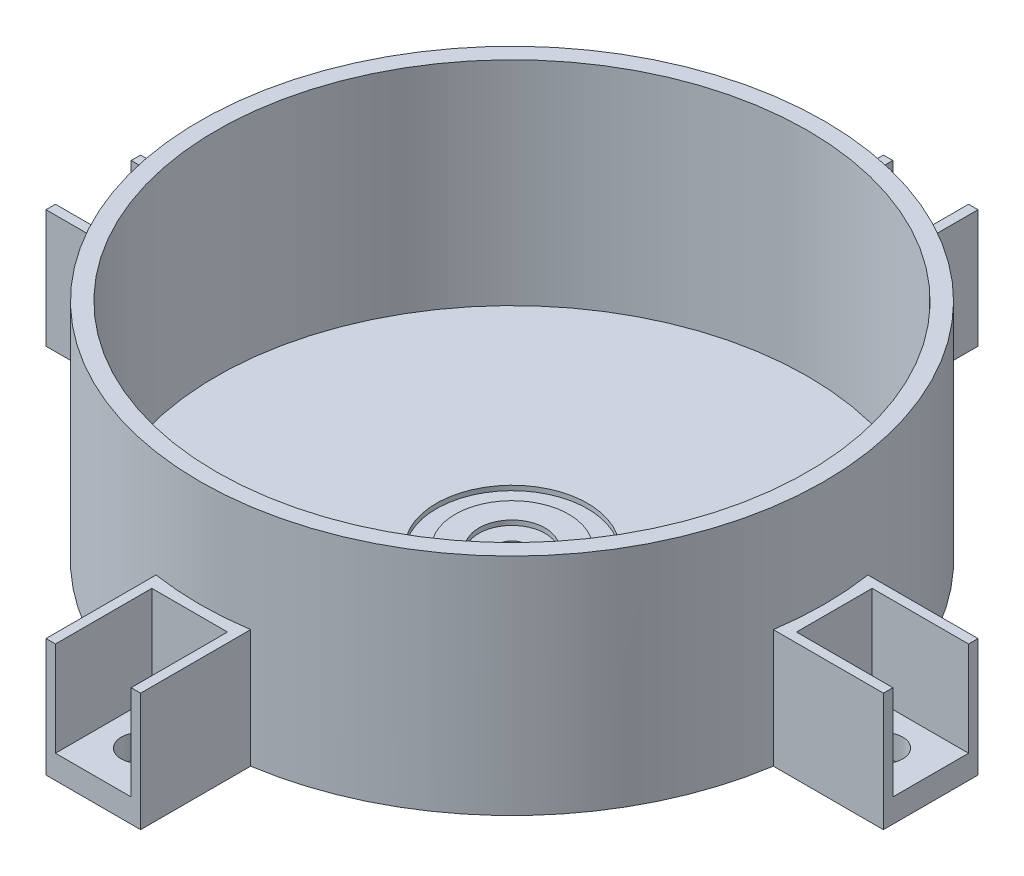
SolidWorks part; units mm, degrees
ref_plane "Front Plane" through (0, 0, 0) normal (0, 0, 1) x (1, 0, 0)
ref_plane "Top Plane" through (0, 0, 0) normal (0, 1, 0) x (1, 0, 0)
ref_plane "Right Plane" through (0, 0, 0) normal (1, 0, 0) x (0, 0, -1)
sketch "Sketch1" plane through (0, 0, 0) normal (0, 1, 0) x (1, 0, 0)
  circle A0 centre (0, 0) radius 132
extrude "Boss-Extrude1" add sketch "Sketch1" along normal blind 5
sketch "Sketch2" plane through (0, 5, 0) normal (0, 1, 0) x (1, 0, 0)
  circle A0 centre (0, 0) radius 125
  circle A1 centre (0, 0) radius 132 construction
  circle A2 centre (0, 0) radius 132
extrude "Boss-Extrude2" add sketch "Sketch2" along normal blind 90
sketch "Sketch3" plane through (0, 0, 0) normal (0, -1, 0) x (1, 0, 0)
  line L0 (-132, 0) -> (-177, 0) construction
  line L1 (-177, -20) -> (-177, 20)
  line L3 (-177, 20) -> (-127.0742, 20)
  line L4 (-177, 20) -> (-177, -20)
  line L5 (-177, -20) -> (-127.0742, -20)
  line L6 (-127.0742, 20) -> (-127.0742, -20)
  circle A0 centre (0, 0) radius 132 construction
  point P9 (-177, 0)
extrude "Boss-Extrude4" add sketch "Sketch3" against normal blind 50 contours L0 L4 L3 | L4 L0 L1 L5
sketch "Sketch4" plane through (0, 50, 0) normal (0, 1, 0) x (1, 0, 0)
  line L0 (-177, 20) -> (-177, -20) construction
  line L1 (-136.2559, -16) -> (-177, -16)
  line L2 (-136.2559, -16) -> (-136.2559, 16)
  line L3 (-136.2559, 16) -> (-177, 16)
  line L4 (-177, -16) -> (-177, 16)
  line L5 (-136.2559, -16) -> (-177, 16) construction
  line L6 (-136.2559, 16) -> (-177, -16) construction
  line L7 (-177, -20) -> (-130.4761, -20) construction
  line L8 (-177, 20) -> (-130.4761, 20) construction
  point P0 (-156.628, 0)
  dimension "D1" = 4
  dimension "D2" = 4
extrude "Cut-Extrude1" cut sketch "Sketch4" against normal blind 40
sketch "Sketch5" plane through (0, 10, 0) normal (0, 1, 0) x (1, 0, 0)
  circle A0 centre (-157.1863, 0) radius 8
extrude "Cut-Extrude2" cut sketch "Sketch5" against normal blind 40
pattern_circular "CirPattern2" count 4 over 360 about axis through (0, 0, 0) along (0, 1, 0) of bodies 106
sketch "Sketch7" plane through (0, 5, 0) normal (0, 1, 0) x (1, 0, 0)
  circle A0 centre (0, 0) radius 32
  circle A1 centre (0, 0) radius 28
extrude "Cut-Extrude3" cut sketch "Sketch7" against normal blind 2
sketch "Sketch8" plane through (0, 5, 0) normal (0, 1, 0) x (1, 0, 0)
  circle A0 centre (0, 0) radius 6
extrude "Cut-Extrude4" cut sketch "Sketch8" against normal blind 3
sketch "Sketch9" plane through (0, 0, 0) normal (0, -1, 0) x (1, 0, 0)
  circle A0 centre (0, 0) radius 32 construction
  circle A1 centre (0, 0) radius 32
extrude "Boss-Extrude5" add sketch "Sketch9" against normal up to surface (5 mm away) up to face at (0, 5, 32)
sketch "Sketch10" plane through (0, 5, 0) normal (0, 1, 0) x (1, 0, 0)
  circle A0 centre (0, 0) radius 32
  circle A1 centre (0, 0) radius 24
extrude "Cut-Extrude5" cut sketch "Sketch10" against normal blind 2
sketch "Sketch11" plane through (0, 5, 0) normal (0, 1, 0) x (1, 0, 0)
  circle A0 centre (0, 0) radius 6
  circle A1 centre (0, 0) radius 14
extrude "Cut-Extrude6" cut sketch "Sketch11" against normal blind 2
sketch "Sketch12" plane through (0, 5, 0) normal (0, 1, 0) x (1, 0, 0)
  circle A0 centre (0, 0) radius 6
extrude "Cut-Extrude7" cut sketch "Sketch12" against normal blind 3
